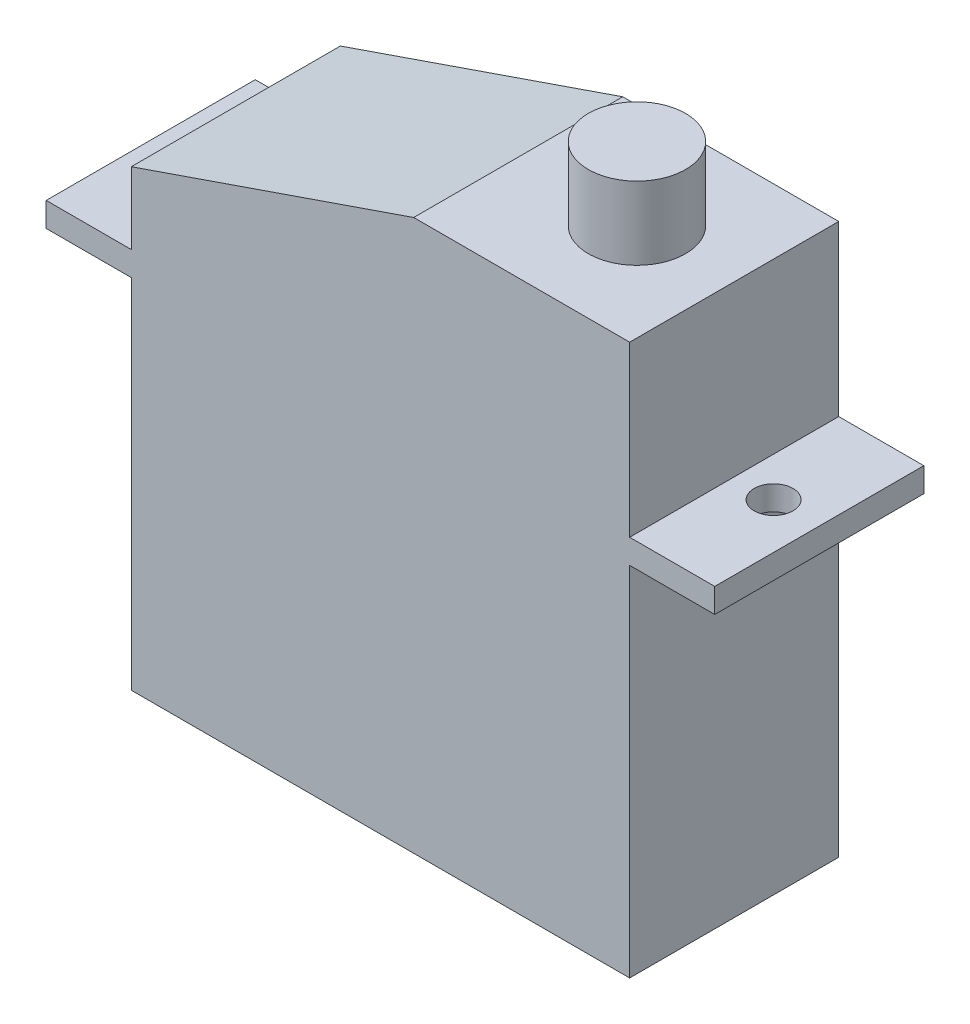
SolidWorks part; units mm, degrees
ref_plane "前视基准面" through (0, 0, 0) normal (0, 0, 1) x (1, 0, 0)
ref_plane "上视基准面" through (0, 0, 0) normal (0, 1, 0) x (1, 0, 0)
ref_plane "右视基准面" through (0, 0, 0) normal (1, 0, 0) x (0, 0, -1)
other "Configuration Table"
sketch "草图1" plane through (0, 0, 0) normal (0, 1, 0) x (1, 0, 0)
  line L1 (0, 0) -> (20.5, 0)
  line L2 (0, 0) -> (0, 8.6)
  line L3 (0, 8.6) -> (20.5, 8.6)
  line L4 (20.5, 0) -> (20.5, 8.6)
  dimension "D1" = 20.5
  dimension "D2" = 8.6
extrude "凸台-拉伸1" add sketch "草图1" along normal blind 15.2
sketch "草图2" plane through (0, 0, 0) normal (0, 0, 1) x (1, 0, 0)
  line L0 (0, 15.2) -> (0, 0) construction
  line L1 (20.5, 15.2) -> (0, 15.2)
  line L2 (20.5, 15.2) -> (20.5, 22.65)
  line L3 (20.5, 22.65) -> (0, 22.65)
  line L4 (0, 15.2) -> (0, 22.65)
  dimension "D1" = 7.45
  dimension "D2" = 0
extrude "凸台-拉伸2" add sketch "草图2" against normal blind 8.6
chamfer "倒角1" distance 4 angle 71 1 edges at (0, 22.65, -4.3)
sketch "草图3" plane through (0, 0, 0) normal (0, 0, 1) x (1, 0, 0)
  line L0 (0, 18.65) -> (0, 0) construction
  line L1 (0, 15.7) -> (-3.5, 15.7)
  line L2 (0, 15.7) -> (0, 14.7)
  line L3 (0, 14.7) -> (-3.5, 14.7)
  line L4 (-3.5, 15.7) -> (-3.5, 14.7)
  line L5 (20.5, 22.65) -> (20.5, 0) construction
  line L6 (20.5, 15.7) -> (24, 15.7)
  line L7 (20.5, 15.7) -> (20.5, 14.7)
  line L8 (20.5, 14.7) -> (24, 14.7)
  line L9 (24, 15.7) -> (24, 14.7)
  line L10 (0, 0) -> (20.5, 0) construction
  point P12 (0, 15.2)
  point P15 (20.5, 15.2)
  dimension "D1" = 15.2
  dimension "D2" = 15.2
  dimension "D3" = 1
  dimension "D4" = 1
  dimension "D5" = 3.5
  dimension "D6" = 3.5
extrude "凸台-拉伸3" add sketch "草图3" against normal blind 8.6
sketch "草图4" plane through (0, 15.7, 0) normal (0, 1, 0) x (1, 0, 0)
  line L1 (-3.5, 8.6) -> (-3.5, 0) construction
  line L2 (24, 8.6) -> (24, 0) construction
  circle A0 centre (-1.62, 4.3) radius 0.8
  circle A1 centre (22.12, 4.3) radius 0.8
  point P6 (-3.5, 4.3)
  point P9 (24, 4.3)
  dimension "D2" = 0
  dimension "D4" = 1.6
  dimension "D6" = 1.6
  dimension "D1" = 0
  dimension "D3" = 1.88
  dimension "D5" = 1.88
extrude "切除-拉伸1" cut sketch "草图4" against normal blind 8.6
sketch "草图5" plane through (0, 22.65, 0) normal (0, 1, 0) x (1, 0, 0)
  line L0 (20.5, 8.6) -> (20.5, 0) construction
  line L1 (20.5, 8.6) -> (20.5, 0) construction
  circle A0 centre (16.5, 4.3) radius 2
  point P4 (20.5, 4.3)
  dimension "D1" = 0
  dimension "D2" = 4
  dimension "D3" = 4
extrude "凸台-拉伸4" add sketch "草图5" along normal blind 3
equation "\"D1@草图2\"=22.65-15.2"
equation "\"D2@草图3\"=\"D1@草图3\""
equation "\"D5@草图3\"=27.5/2-20.5/2"
equation "\"D6@草图3\"=\"D5@草图3\""
equation "\"D3@草图4\"=27.5/2-23.74/2"
equation "\"D5@草图4\"=\"D3@草图4\""
